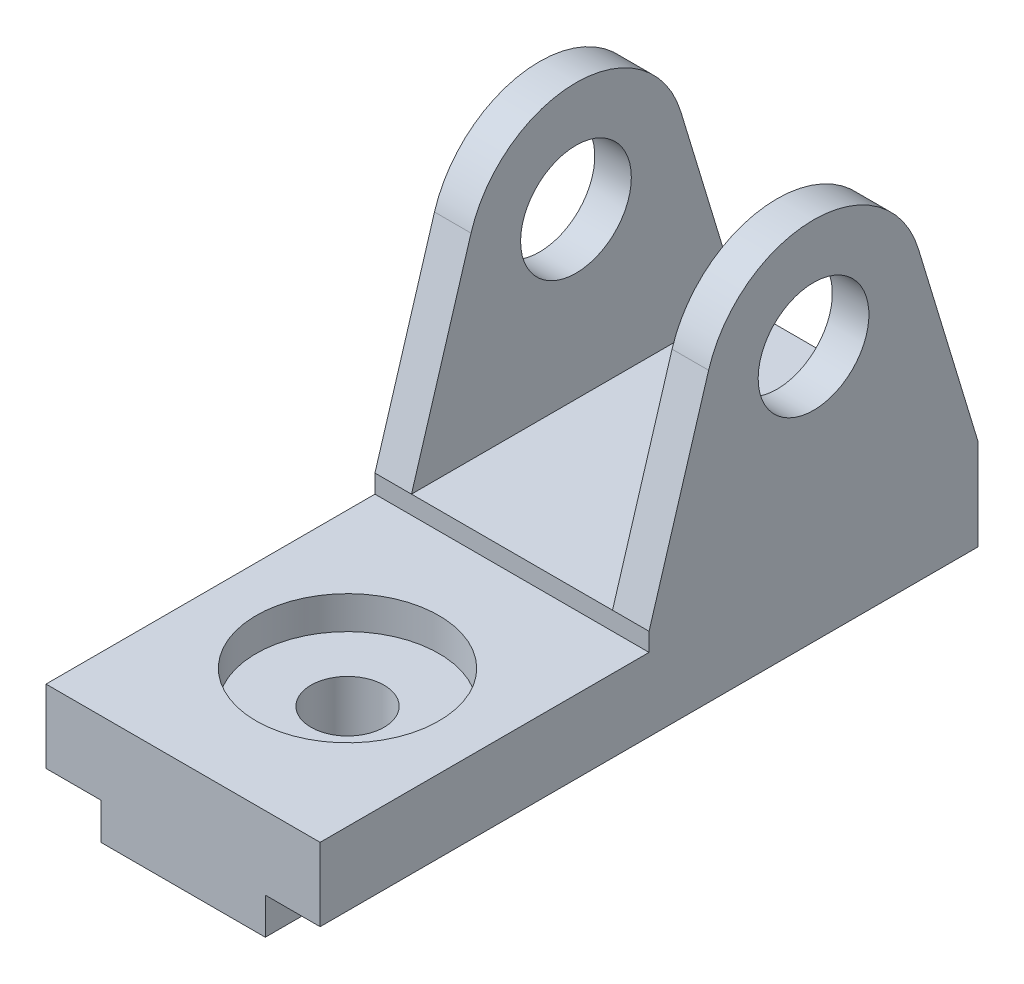
SolidWorks part; units mm, degrees
ref_plane "Front Plane" through (0, 0, 0) normal (0, 0, 1) x (1, 0, 0)
ref_plane "Top Plane" through (0, 0, 0) normal (0, 1, 0) x (1, 0, 0)
ref_plane "Right Plane" through (0, 0, 0) normal (1, 0, 0) x (0, 0, -1)
sketch "Sketch1" plane through (0, 0, 0) normal (0, 1, 0) x (1, 0, 0)
  line L1 (-37.5, 90) -> (37.5, 90)
  line L2 (-37.5, 90) -> (-37.5, -90)
  line L3 (-37.5, -90) -> (37.5, -90)
  line L4 (37.5, 90) -> (37.5, -90)
  line L5 (-37.5, 90) -> (37.5, -90) construction
  line L6 (-37.5, -90) -> (37.5, 90) construction
  point P0 (0, 0)
  dimension "D1" = 75
  dimension "D2" = 180
extrude "Boss-Extrude1" add sketch "Sketch1" along normal blind 30
sketch "Sketch2" plane through (0, 0, 90) normal (0, 0, 1) x (1, 0, 0)
  line L0 (-37.5, 0) -> (37.5, 0) construction
  line L2 (-22.5, 0) -> (-22.5, 10)
  line L5 (0, 0) -> (0, 21.1449) construction
  line L6 (-22.5, 10) -> (-37.5, 10)
  line L7 (-37.5, 30) -> (-37.5, 0) construction
  line L8 (-37.5, 10) -> (-37.5, 0)
  line L9 (-37.5, 0) -> (-22.5, 0)
  dimension "D1" = 22.5
  dimension "D2" = 10
extrude "Cut-Extrude1" cut sketch "Sketch2" against normal through all
mirror "Mirror1" about plane through (0, 0, 0) normal (1, 0, 0) of "Cut-Extrude1"
sketch "Sketch3" plane through (-37.5, 0, 0) normal (-1, 0, 0) x (0, 0, 1)
  line L0 (-90, 30) -> (-90, 35)
  line L1 (90, 30) -> (90, 10) construction
  line L2 (-90, 35) -> (-73.7083, 88.7083)
  line L3 (-45, 80) -> (-45, -29.0922) construction
  line L4 (0, 30) -> (0, 35)
  line L5 (0, 35) -> (-16.2917, 88.7083)
  line L6 (-90, 30) -> (0, 30)
  line L7 (-90, 0) -> (90, 0) construction
  arc A0 (-16.2917, 88.7083) -> (-73.7083, 88.7083) centre (-45, 80) ccw
  circle A1 centre (-45, 80) radius 15.1496
  dimension "D1" = 60
  dimension "D5" = 30.2992
  dimension "D2" = 80
  dimension "D3" = 135
  dimension "D4" = 35
extrude "Boss-Extrude2" add sketch "Sketch3" against normal up to surface (75 mm away) up to face at (37.5, 20, 0)
sketch "Sketch4" plane through (0, 30, 0) normal (0, 1, 0) x (1, 0, 0)
  line L0 (37.5, 0) -> (-37.5, 0) construction
  line L1 (-27.5, 0) -> (27.5, 0)
  line L2 (-27.5, 0) -> (-27.5, 90)
  line L3 (-27.5, 90) -> (27.5, 90)
  line L4 (27.5, 0) -> (27.5, 90)
  line L5 (0, 0) -> (0, 61.4011) construction
  line L6 (37.5, 90) -> (-37.5, 90) construction
  dimension "D1" = 55
extrude "Cut-Extrude2" cut sketch "Sketch4" along normal through all from offset 5
hole_wizard "Hole1" positions "Sketch5" profile "Sketch6" legacy end condition through all
sketch "Sketch5" plane through (0, 30, 0) normal (0, 1, 0) x (1, 0, 0)
  line L0 (-37.5, -90) -> (37.5, -90) construction
  point P0 (0, -45)
  point P7 (0, 0)
  dimension "D1" = 45
sketch "Sketch6" plane through (0, 30, 45) normal (1, 0, 0) x (0, 0, 1)
  line L0 (0, 0) -> (0, 30)
  line L1 (0, 30) -> (10, 30)
  line L2 (10, 30) -> (10, 9)
  line L3 (10, 9) -> (25, 9)
  line L4 (25, 9) -> (25, 0)
  line L5 (25, 0) -> (0, 0)
  line L6 (0, 110) -> (0, -10) construction
  dimension "Diameter" = 20
  dimension "Depth" = 30
  dimension "C-Bore Diameter" = 50
  dimension "C-Bore Depth" = 9
